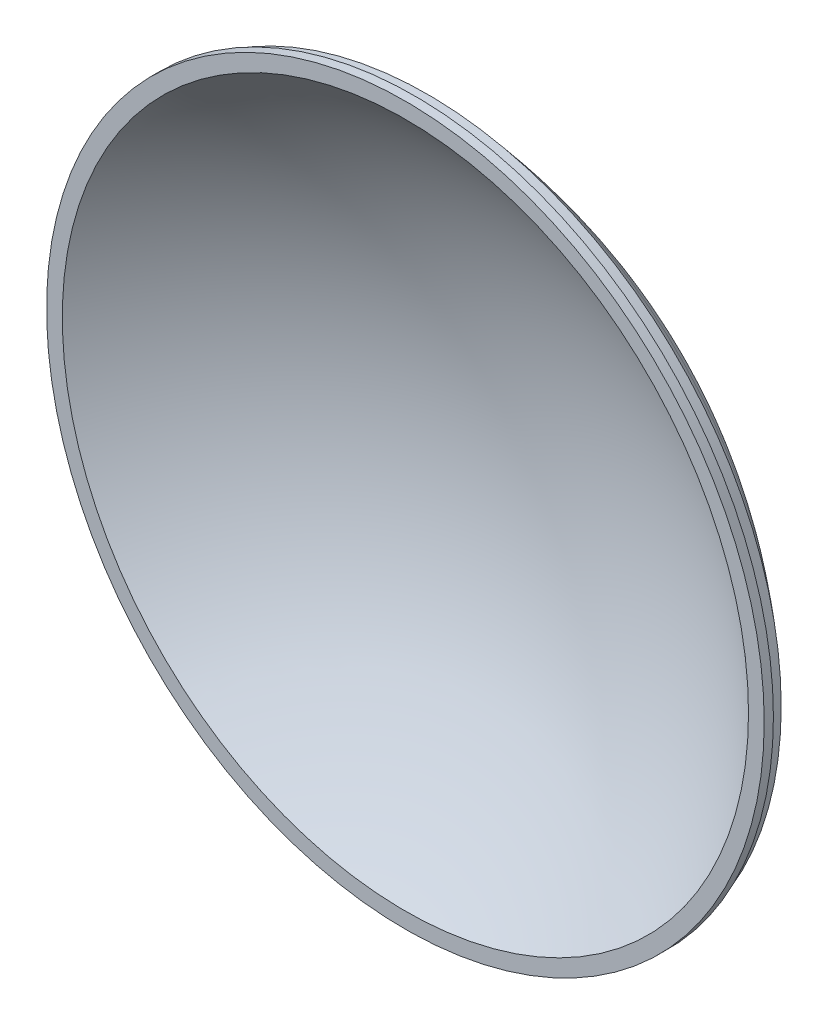
SolidWorks part; units mm, degrees
ref_plane "Front" through (0, 0, 0) normal (0, 0, 1) x (1, 0, 0)
ref_plane "Top" through (0, 0, 0) normal (0, 1, 0) x (1, 0, 0)
ref_plane "Right" through (0, 0, 0) normal (1, 0, 0) x (0, 0, -1)
sketch "Sketch1" plane through (0, 0, 0) normal (0, 1, 0) x (1, 0, 0)
  line L0 (0, 0) -> (0, -94.18) construction
  line L1 (0, -94.18) -> (233.083, -94.18) construction
  line L2 (233.083, -94.18) -> (243.753, -94.18)
  line L3 (243.753, -94.18) -> (243.753, -87.93)
  line L4 (243.753, -87.93) -> (240.353, -87.93)
  line L5 (240.353, -87.93) -> (240.353, -79.23)
  line L6 (228.3409, -69.061) -> (228.3409, -69.061)
  line L7 (228.3409, -69.061) -> (228.3409, -69.061)
  line L8 (228.3409, -69.061) -> (228.3409, -69.061)
  line L9 (228.3409, -69.061) -> (228.3409, -69.061)
  line L10 (0, 0) -> (-0.0081, 15.7385)
  line L11 (-0.0081, 15.7385) -> (0, 0) construction
  arc A0 (228.3409, -69.061) -> (240.353, -79.23) centre (-662.4231, -1133.4489) cw
  spline S0 degree 4 poles (-40, -2.4078) (-39.3727, -2.3323) (-36.2353, -1.9628) (-32.465, -1.5666) (-28.0598, -1.1706) (-23.9644, -0.8644) (-22.0734, -0.7349) (-20.1923, -0.6155) (-18.3213, -0.5061) (-16.1447, -0.3923) (-13.6626, -0.2809) (-11.4896, -0.1995) (-9.6274, -0.1412) (-8.0752, -0.1002) (-6.8308, -0.072) (-5.587, -0.0484) (-4.3581, -0.0294) (-3.127, -0.015) (-1.8052, -0.0051) (-0.4589, 0.0002) (0.348, 0.0006) (1.3095, -0.0018) (2.3133, -0.0065) (3.2977, -0.0136) (4.6864, -0.0285) (6.5475, -0.0577) (8.7434, -0.1054) (11.2327, -0.1784) (13.7316, -0.27) (16.2245, -0.3802) (18.7192, -0.509) (21.2114, -0.6564) (23.7033, -0.8225) (26.1934, -1.0071) (28.6823, -1.2104) (31.1695, -1.4324) (33.655, -1.6729) (36.1386, -1.9321) (41.7222, -2.5573) (50.3876, -3.7037) (62.0933, -5.6434) (76.7526, -8.7632) (90.0458, -12.2336) (101.991, -15.8772) (112.6171, -19.5365) (121.9592, -23.0752) (131.1897, -26.8956) (140.3007, -30.9926) (151.5311, -36.4525) (164.7408, -43.533) (179.7363, -52.5331) (196.2674, -63.7669) (212.1673, -75.8759) (227.424, -88.7845) (242.0364, -102.4167) (255.4611, -116.1344) (267.7932, -129.7938) (279.6314, -143.8819) (290.9932, -158.3572) (302.3394, -173.835) (313.6285, -190.3198) (324.4233, -207.1319) (333.462, -222.0955) (340.9366, -235.0813) (346.9921, -246.0003) (351.7357, -254.7905) (356.382, -263.6327) (360.9338, -272.5237) (365.3944, -281.4609) (369.7666, -290.4415) (374.0534, -299.4635) (378.2572, -308.5239) (381.8659, -316.4846) (384.91, -323.3285) (387.416, -329.0478) (389.4007, -333.6275) (391.3703, -338.2231) (393.3157, -342.8112) (395.0137, -346.8599) (396.3169, -349.994) (397.3036, -352.3835) (398.1311, -354.3894) (399.5533, -357.8691) (400.2619, -359.61) (402.1345, -364.2448) (403.2476, -367.0323) (404.6818, -370.6337) (405.9179, -373.7708) (407.2566, -377.1836) (408.5227, -380.4407) (409.8181, -383.7924) (411.085, -387.0963) (412.6718, -391.2615) (414.5532, -396.2473) (416.4205, -401.2519) (418.266, -406.2552) (419.4882, -409.5982) (420.0964, -411.269) (420.4, -412.105) knots 0 0 0 0 0 0.003772 0.018859 0.022631 0.026403 0.028289 0.030175 0.033883 0.037592 0.0413 0.045009 0.046863 0.048717 0.050571 0.052426 0.05428 0.056134 0.057988 0.059843 0.061706 0.062638 0.063569 0.065433 0.067296 0.071023 0.07475 0.078477 0.082204 0.085931 0.089657 0.093384 0.097111 0.100838 0.104565 0.108292 0.112018 0.115745 0.119472 0.141833 0.164194 0.186555 0.208916 0.223824 0.238731 0.253638 0.268546 0.283453 0.298361 0.328175 0.35799 0.387805 0.417619 0.447434 0.477249 0.507064 0.532167 0.557271 0.587086 0.6169 0.646715 0.67653 0.706345 0.721252 0.736159 0.751067 0.765974 0.780882 0.795789 0.810696 0.825604 0.840511 0.855418 0.862872 0.870326 0.877779 0.885233 0.892687 0.900141 0.903867 0.905731 0.907594 0.915048 0.920357 0.925667 0.930976 0.936286 0.941595 0.946905 0.952214 0.957524 0.962833 0.968143 0.978762 0.989381 0.99469 1 1 1 1 1 construction
  spline S1 degree 4 poles (0, 0) (0.2669, 0.0001) (0.6675, -0.0002) (1.3095, -0.0018) (2.3133, -0.0065) (3.2977, -0.0136) (4.6864, -0.0285) (6.5475, -0.0577) (8.7434, -0.1054) (11.2327, -0.1784) (13.7316, -0.27) (16.2245, -0.3802) (18.7192, -0.509) (21.2114, -0.6564) (23.7033, -0.8225) (26.1934, -1.0071) (28.6823, -1.2104) (31.1695, -1.4324) (33.655, -1.6729) (36.1386, -1.9321) (41.7222, -2.5573) (50.3876, -3.7037) (62.0933, -5.6434) (76.7526, -8.7632) (90.0458, -12.2336) (101.991, -15.8772) (112.6171, -19.5365) (121.9592, -23.0752) (131.1897, -26.8956) (140.3007, -30.9926) (151.5311, -36.4525) (164.7408, -43.533) (179.7363, -52.5331) (196.2674, -63.7669) (211.7348, -75.5465) (222.7791, -84.8559) (229.8115, -91.1623) (233.083, -94.18) knots 0.059843 0.059843 0.059843 0.059843 0.059843 0.061706 0.062638 0.063569 0.065433 0.067296 0.071023 0.07475 0.078477 0.082204 0.085931 0.089657 0.093384 0.097111 0.100838 0.104565 0.108292 0.112018 0.115745 0.119472 0.141833 0.164194 0.186555 0.208916 0.223824 0.238731 0.253638 0.268546 0.283453 0.298361 0.328175 0.35799 0.387805 0.417619 0.44419 0.44419 0.44419 0.44419 0.44419
  spline S2 degree 1 poles (-0.0081, 15.7385) (228.3409, -69.061) knots 0 0 1 1 construction
  spline S3 degree 3 poles (-0.0081, 15.7385) (0.2857, 15.7386) (0.8408, 15.738) (1.8684, 15.7345) (2.9012, 15.7284) (4.2276, 15.7164) (5.8214, 15.6948) (8.4162, 15.6461) (11.6581, 15.558) (16.8401, 15.3598) (23.3132, 15.0042) (33.657, 14.205) (46.5504, 12.7737) (77.3172, 7.9562) (122.5694, -4.4794) (169.4623, -27.1431) (204.1314, -49.8057) (220.4331, -62.4431) (228.3409, -69.061) knots 0.059843 0.059843 0.059843 0.059843 0.061229 0.062615 0.064001 0.065387 0.068159 0.070932 0.076476 0.082021 0.09311 0.104199 0.126377 0.148555 0.237267 0.325979 0.370335 0.414691 0.414691 0.414691 0.414691
  dimension "D1" = 94.18
  dimension "D2" = 10.67
  dimension "D3" = 6.25
  dimension "D4" = 3.4
  dimension "D5" = 8.7
  dimension "D6" = 15.7385
revolve "Revolve2" add sketch "Sketch1" angle 360 about L10
